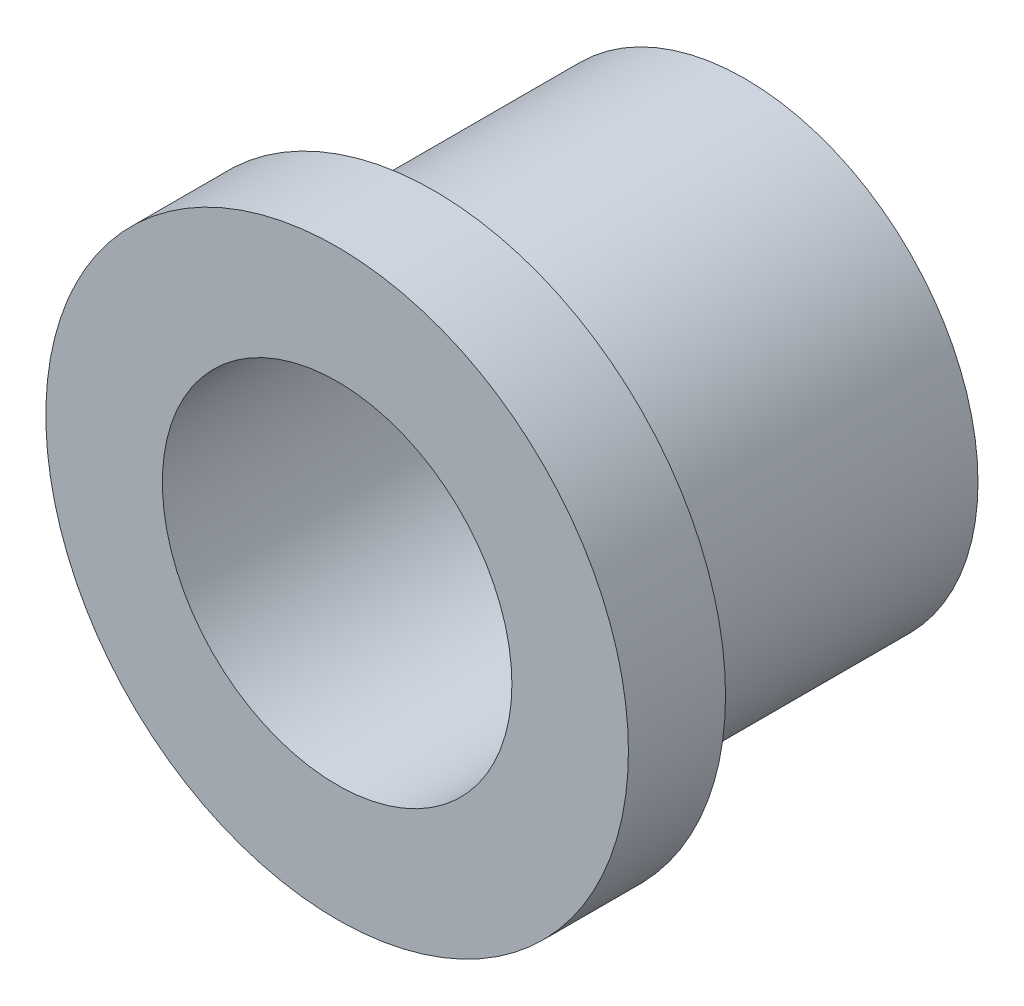
SolidWorks part; units mm, degrees
ref_plane "Front Plane" through (0, 0, 0) normal (0, 0, 1) x (1, 0, 0)
ref_plane "Top Plane" through (0, 0, 0) normal (0, 1, 0) x (1, 0, 0)
ref_plane "Right Plane" through (0, 0, 0) normal (1, 0, 0) x (0, 0, -1)
sketch "Sketch2" plane through (0, 0, 0) normal (0, 0, 1) x (1, 0, 0)
  line L0 (0, 93.3446) -> (0, -93.3446) construction
  line L1 (-51.599, 0) -> (51.504, 0) construction
  circle A2 centre (0, 0) radius 9
  circle A3 centre (0, 0) radius 12
  dimension "D1" = 18
  dimension "D2" = 3
extrude "Boss-Extrude1" add sketch "Sketch2" along normal mid plane 16 separate body
sketch "Sketch3" plane through (0, 0, 8) normal (0, 0, 1) x (1, 0, 0)
  circle A0 centre (0, 0) radius 9
  circle A1 centre (0, 0) radius 15
  dimension "D1" = 30
  dimension "D2" = 18
extrude "Boss-Extrude2" add sketch "Sketch3" along normal blind 5 separate body
